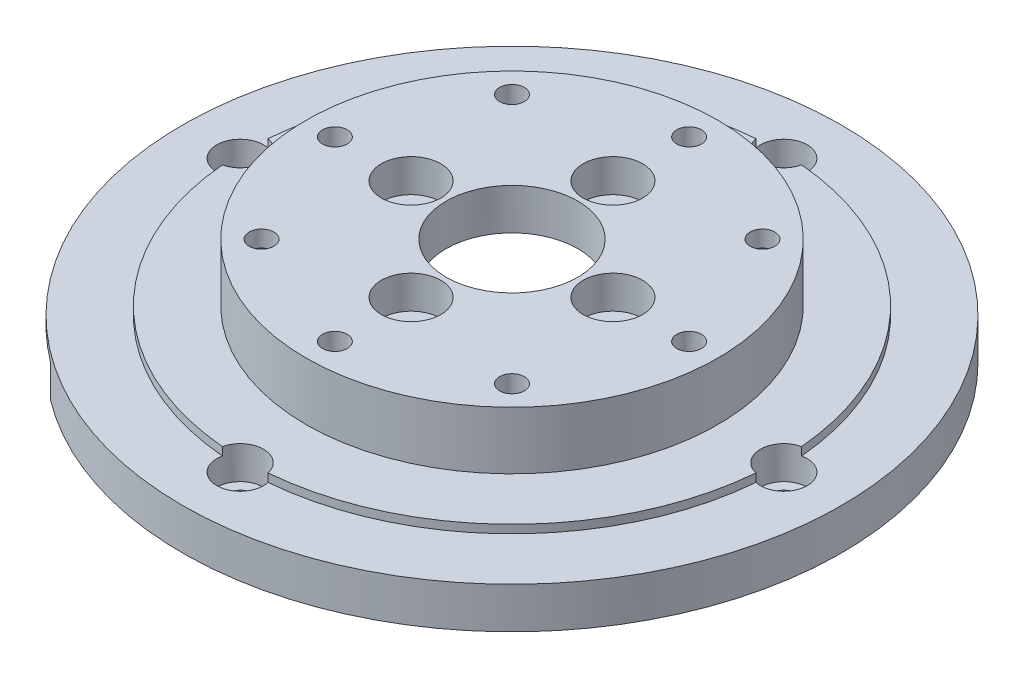
SolidWorks part; units mm, degrees
ref_plane "Front Plane" through (0, 0, 0) normal (0, 0, 1) x (1, 0, 0)
ref_plane "Top Plane" through (0, 0, 0) normal (0, 1, 0) x (1, 0, 0)
ref_plane "Right Plane" through (0, 0, 0) normal (1, 0, 0) x (0, 0, -1)
sketch "Sketch1" plane through (0, 0, 0) normal (0, 1, 0) x (1, 0, 0)
  circle A0 centre (0, 0) radius 40
  circle A2 centre (0, 0) radius 33 construction
  circle A13 centre (0, 0) radius 27.5 construction
  circle A19 centre (0.001, 0.001) radius 27.5 construction
  circle A25 centre (0.002, 0) radius 27.5 construction
  circle A31 centre (0.001, -0.001) radius 27.5 construction
  point P14 (0, 0)
  point P25 (0, 0)
  point P64 (0.001, 0)
  dimension "D1" = 80
  dimension "D3" = 66
  dimension "D6" = 55
  dimension "D10" = 4
extrude "Boss-Extrude1" add sketch "Sketch1" along normal blind 5
sketch "Sketch4" plane through (0, 5, 0) normal (0, 1, 0) x (1, 0, 0)
  circle A0 centre (0, 0) radius 32.5
  dimension "D1" = 65
extrude "Boss-Extrude2" add sketch "Sketch4" along normal blind 1
sketch "Sketch5" plane through (0, 6, 0) normal (0, 1, 0) x (1, 0, 0)
  circle A0 centre (0, 0) radius 25
  dimension "D1" = 50
extrude "Boss-Extrude3" add sketch "Sketch5" along normal blind 7
sketch "Sketch6" plane through (0, 13, 0) normal (0, 1, 0) x (1, 0, 0)
  circle A0 centre (0, 0) radius 12.25 construction
  circle A1 centre (12.25, 0) radius 2
  circle A2 centre (0, -12.25) radius 2
  circle A3 centre (-12.25, 0) radius 2
  circle A4 centre (0, 12.25) radius 2
  circle A5 centre (0, 0) radius 8
  point P14 (0, 0)
  dimension "D1" = 24.5
  dimension "D2" = 4
  dimension "D4" = 16
  dimension "D3" = 4
extrude "Cut-Extrude1" cut sketch "Sketch6" against normal through all
sketch "Sketch7" plane through (0, 0, 0) normal (0, -1, 0) x (1, 0, 0)
  circle A0 centre (0, 0) radius 30
  dimension "D1" = 60
extrude "Cut-Extrude2" cut sketch "Sketch7" against normal blind 4
sketch "Sketch8" plane through (0, 4, 0) normal (0, -1, 0) x (1, 0, 0)
  circle A0 centre (0, 0) radius 24
  dimension "D1" = 48
extrude "Cut-Extrude3" cut sketch "Sketch8" against normal blind 4
sketch "Sketch9" plane through (0, 13, 0) normal (0, 1, 0) x (1, 0, 0)
  circle A0 centre (0, 12.25) radius 3.61
  circle A1 centre (12.25, 0) radius 3.61
  circle A2 centre (0, -12.25) radius 3.61
  circle A3 centre (-12.25, 0) radius 3.61
  point P12 (0, 0)
  dimension "D1" = 7.22
  dimension "D2" = 4
extrude "Cut-Extrude4" cut sketch "Sketch9" against normal blind 4
sketch "Sketch10" plane through (0, 13, 0) normal (0, 1, 0) x (1, 0, 0)
  circle A0 centre (0, 0) radius 33 construction
  circle A1 centre (0, 33) radius 1.57
  circle A2 centre (33, 0) radius 1.57
  circle A3 centre (0, -33) radius 1.57
  circle A4 centre (-33, 0) radius 1.57
  point P14 (0, 0)
  dimension "D1" = 66
  dimension "D2" = 3.14
  dimension "D3" = 4
extrude "Cut-Extrude5" cut sketch "Sketch10" against normal through all
sketch "Sketch11" plane through (0, 6, 0) normal (0, 1, 0) x (1, 0, 0)
  circle A0 centre (0, 33) radius 2.84
  circle A1 centre (33, 0) radius 2.84
  circle A2 centre (0, -33) radius 2.84
  circle A3 centre (-33, 0) radius 2.84
  point P12 (0, 0)
  dimension "D1" = 5.68
  dimension "D2" = 4
extrude "Cut-Extrude6" cut sketch "Sketch11" against normal blind 4
sketch "Sketch12" plane through (0, 13, 0) normal (0, 1, 0) x (1, 0, 0)
  circle A0 centre (0, 0) radius 21.5 construction
  circle A1 centre (0, -21.5) radius 1.5
  circle A2 centre (-15.2028, -15.2028) radius 1.5
  circle A3 centre (-21.5, 0) radius 1.5
  circle A4 centre (-15.2028, 15.2028) radius 1.5
  circle A5 centre (0, 21.5) radius 1.5
  circle A6 centre (15.2028, 15.2028) radius 1.5
  circle A7 centre (21.5, 0) radius 1.5
  circle A8 centre (15.2028, -15.2028) radius 1.5
  point P22 (0, 0)
  dimension "D1" = 43
  dimension "D2" = 3
  dimension "D3" = 8
extrude "Cut-Extrude7" cut sketch "Sketch12" against normal blind 4
sketch "Sketch13" plane through (0, 4, 0) normal (0, -1, 0) x (1, 0, 0)
  line L1 (15.2028, -11.9696) -> (12.4028, -13.5862)
  line L2 (12.4028, -13.5862) -> (12.4028, -16.8194)
  line L3 (12.4028, -16.8194) -> (15.2028, -18.436)
  line L4 (15.2028, -18.436) -> (18.0028, -16.8194)
  line L5 (18.0028, -16.8194) -> (18.0028, -13.5862)
  line L6 (18.0028, -13.5862) -> (15.2028, -11.9696)
  line L7 (-15.2028, 11.9696) -> (-12.4028, 13.5862)
  line L8 (-12.4028, 13.5862) -> (-12.4028, 16.8194)
  line L9 (-12.4028, 16.8194) -> (-15.2028, 18.436)
  line L10 (-15.2028, 18.436) -> (-18.0028, 16.8194)
  line L11 (-18.0028, 16.8194) -> (-18.0028, 13.5862)
  line L12 (-18.0028, 13.5862) -> (-15.2028, 11.9696)
  circle A0 centre (15.2028, -15.2028) radius 1.5 construction
  circle A1 centre (15.2028, -15.2028) radius 1.5 construction
  circle A2 centre (-15.2028, 15.2028) radius 1.5 construction
  circle A3 centre (-15.2028, 15.2028) radius 1.5 construction
  circle A4 centre (15.2028, -15.2028) radius 2.8 construction
  circle A5 centre (-15.2028, 15.2028) radius 2.8 construction
  dimension "D1" = 5.6
  dimension "D2" = 5.6
extrude "Cut-Extrude9" cut sketch "Sketch13" against normal blind 7
sketch "Sketch14" plane through (0, 0, 0) normal (0, -1, 0) x (1, 0, 0)
  line L0 (-21.2132, 21.2132) -> (-28.2843, 28.2843) construction
  line L1 (0, 0) -> (-57.1659, 0) construction
  line L2 (-16.9646, 24.7427) -> (-24.1265, 31.9047)
  line L3 (-3.8891, -3.8891) -> (-7.7782, 0)
  line L4 (0, 0) -> (-35.6763, 35.6763) construction
  line L5 (3.8891, 3.8891) -> (-31.7872, 39.5653) construction
  line L6 (-3.8891, -3.8891) -> (-39.5653, 31.7872) construction
  line L7 (-24.7427, 16.9646) -> (-31.9047, 24.1265)
  circle A0 centre (0, 0) radius 30 construction
  circle A1 centre (0, 0) radius 40 construction
  circle A2 centre (0, 0) radius 30
  circle A3 centre (0, 0) radius 40
  circle M9 centre (0, 0) radius 30
  circle M10 centre (0, 0) radius 40
  dimension "D1" = 45
  dimension "D2" = 5.5
  dimension "D3" = 5.5
extrude "Cut-Extrude10" cut sketch "Sketch14" against normal up to surface (4 mm away) contours L7 L2 M9 M10
